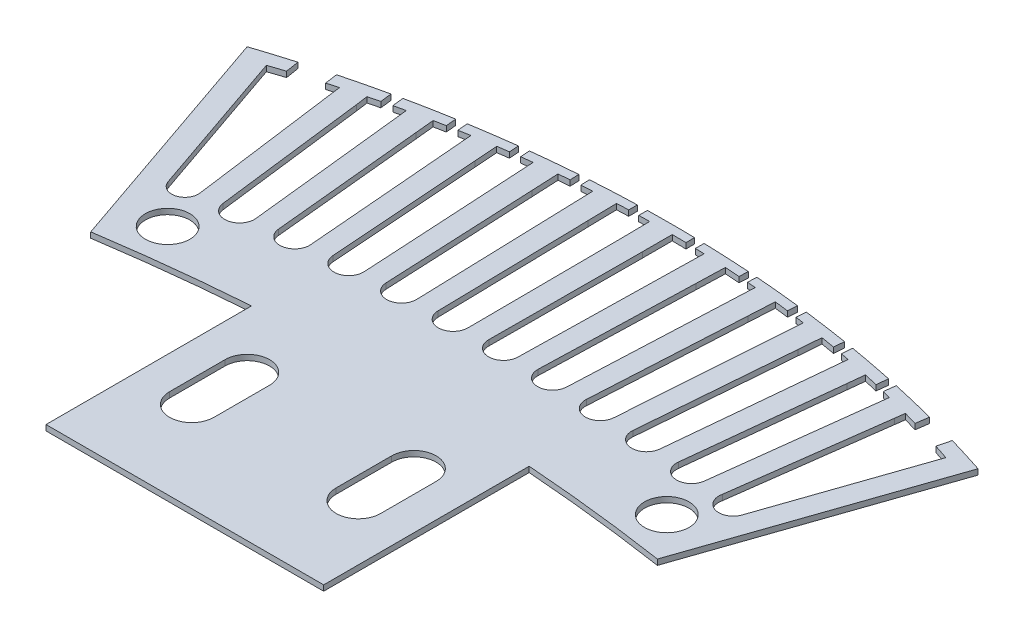
SolidWorks part; units mm, degrees
material "Galvanized Steel"
ref_plane "Front Plane" through (0, 0, 0) normal (0, 0, 1) x (1, 0, 0)
ref_plane "Top Plane" through (0, 0, 0) normal (0, 1, 0) x (1, 0, 0)
ref_plane "Right Plane" through (0, 0, 0) normal (1, 0, 0) x (0, 0, -1)
sketch "Sketch1" plane through (0, 0, 0) normal (0, 1, 0) x (1, 0, 0)
  line L0 (-1000, 0) -> (335, 0) construction
  line L1 (0, -681.9239) -> (0, 0) construction
  line L2 (-500, -866.0254) -> (24500, 42435.2448) construction
  line L3 (-500, 866.0254) -> (24500, -42435.2448) construction
  line L94 (65.8024, 379.335) -> (51.0159, 336.3919)
  line L247 (-65.8024, 379.335) -> (-51.0159, 336.3919)
  line L252 (-45.727, 348.0815) -> (-42.7621, 333.287) construction
  line L253 (0, -1000) -> (0, 49000) construction
  line L254 (-58.4419, 379.0785) -> (-58.8238, 381.4977)
  line L261 (-25, 339.3186) -> (-25, 302.3186)
  line L262 (-25, 302.3186) -> (25, 302.3186)
  line L263 (25, 339.3186) -> (25, 302.3186)
  line L280 (-61.1702, 378.1684) -> (-51.8767, 351.178)
  line L288 (-50.8939, 379.6161) -> (-47.2288, 352.2783)
  line L291 (-46.9266, 380.1269) -> (-43.5472, 352.7523)
  line L301 (58.4908, 379.0626) -> (59.0948, 381.4187)
  line L302 (-41.2051, 380.7896) -> (-38.2377, 353.3673)
  line L308 (-37.2261, 381.1992) -> (-34.5453, 353.7473)
  line L309 (-31.4895, 381.7158) -> (-29.2218, 354.2268)
  line L315 (-27.5014, 382.0239) -> (-25.5209, 354.5127)
  line L316 (-21.7536, 382.3943) -> (-20.187, 354.8564)
  line L322 (-17.7589, 382.6006) -> (-16.48, 355.0478)
  line L323 (-12.0035, 382.8244) -> (-11.139, 355.2555)
  line L329 (-8.0048, 382.9288) -> (-7.4284, 355.3525)
  line L330 (-2.2456, 383.0059) -> (-2.0838, 355.424)
  line L336 (1.7544, 383.0085) -> (1.6281, 355.4264)
  line L337 (7.5138, 382.9388) -> (6.9727, 355.3617)
  line L343 (11.5126, 382.8394) -> (10.6835, 355.2695)
  line L344 (17.2683, 382.623) -> (16.0247, 355.0687)
  line L350 (21.2632, 382.4218) -> (19.732, 354.882)
  line L351 (27.0115, 382.0588) -> (25.0663, 354.5451)
  line L352 (31.0001, 381.7559) -> (28.7676, 354.264)
  line L353 (36.7373, 381.2466) -> (34.0917, 353.7913)
  line L354 (40.7168, 380.8421) -> (37.7846, 353.416)
  line L358 (46.4391, 380.1868) -> (43.0949, 352.8079)
  line L373 (50.407, 379.6811) -> (46.777, 352.3386)
  line L374 (0, 0) -> (-49.2136, 349.5919) construction
  line L375 (-53.3884, 383.0131) -> (-53.0712, 380.7369)
  line L376 (61.1702, 378.1684) -> (51.8767, 351.178)
  line L377 (-45.4809, 384.9235) -> (-45.2357, 382.8479)
  line L378 (-43.5005, 383.2669) -> (-43.7316, 385.3027)
  line L379 (-35.5666, 384.9644) -> (-35.7398, 386.8388)
  line L380 (-33.8121, 385.292) -> (-33.9739, 387.1353)
  line L381 (-25.8013, 386.5717) -> (-25.9162, 388.2933)
  line L382 (-24.0323, 386.8069) -> (-24.1379, 388.5062)
  line L383 (-15.9663, 387.6655) -> (-16.0329, 389.283)
  line L385 (-6.0052, 388.2457) -> (-6.0052, 389.8087)
  line L390 (14.2976, 387.7995) -> (14.3915, 389.402)
  line L391 (-14.1876, 387.8078) -> (-14.2462, 389.4119)
  line L392 (-15, 302.3186) -> (-15, 318.5686) construction
  line L393 (-19, 328.5686) -> (-19, 318.5686)
  line L395 (-4.2458, 389.8516) -> (-4.2458, 388.2934)
  line L396 (4.2458, 389.8516) -> (4.2458, 388.2934)
  line L397 (6.0052, 388.2457) -> (6.0052, 389.8087)
  line L399 (15.9663, 387.6655) -> (16.0329, 389.283)
  line L400 (24.0323, 386.8069) -> (24.1379, 388.5062)
  line L401 (25.8013, 386.5717) -> (25.9162, 388.2933)
  line L402 (33.8121, 385.292) -> (33.9739, 387.1353)
  line L403 (35.5666, 384.9644) -> (35.7398, 386.8388)
  line L404 (43.5005, 383.2669) -> (43.7316, 385.3027)
  line L405 (45.4809, 384.9235) -> (45.2357, 382.8478)
  line L406 (53.3884, 383.0131) -> (53.0712, 380.7369)
  line L407 (-11, 328.5686) -> (-11, 318.5686)
  line L408 (19, 328.5686) -> (19, 318.5686)
  line L409 (11, 328.5686) -> (11, 318.5686)
  line L410 (-50.8939, 379.6161) -> (-51.1192, 381.2967)
  line L411 (-46.9266, 380.1269) -> (-47.2288, 382.345)
  line L412 (-41.2051, 380.7896) -> (-41.5226, 383.7235)
  line L413 (-37.2261, 381.1992) -> (-37.5555, 384.5722)
  line L414 (-31.4895, 381.7158) -> (-31.8136, 385.6443)
  line L415 (-27.5014, 382.0239) -> (-27.8081, 386.2841)
  line L416 (-21.7536, 382.3943) -> (-22.0187, 387.0541)
  line L417 (-17.7589, 382.6006) -> (-17.9855, 387.4834)
  line L418 (-12.0035, 382.8244) -> (-12.1596, 387.9495)
  line L419 (-8.0048, 382.9288) -> (-8.1143, 388.1668)
  line L420 (7.5138, 382.9388) -> (7.6168, 388.1875)
  line L421 (11.5126, 382.8394) -> (11.6672, 387.9806)
  line L422 (17.2683, 382.623) -> (17.4897, 387.5301)
  line L423 (21.2632, 382.4218) -> (21.524, 387.1115)
  line L424 (27.0115, 382.0588) -> (27.3154, 386.3568)
  line L425 (31.0001, 381.7559) -> (31.3226, 385.7275)
  line L426 (36.7373, 381.2466) -> (37.0672, 384.6706)
  line L427 (40.7168, 380.8421) -> (41.0365, 383.8323)
  line L428 (46.4391, 380.1868) -> (46.7187, 382.4759)
  line L429 (50.407, 379.6811) -> (50.64, 381.4306)
  line L430 (-2.2456, 383.0059) -> (-2.3106, 388.327)
  line L431 (1.7544, 383.0085) -> (1.7544, 388.3329)
  arc A44 (-167.5, 290.1185) -> (167.5, 290.1185) centre (0, 0) ccw construction
  circle A114 centre (-44.941, 344.1595) radius 4
  circle A115 centre (44.941, 344.1595) radius 4
  arc A145 (-47.2288, 352.2783) -> (-49.2136, 349.5919) centre (-49.6075, 351.9594) cw
  arc A146 (-51.8767, 351.178) -> (-49.2136, 349.5919) centre (-49.6075, 351.9594) ccw
  arc A149 (-19, 318.5686) -> (-11, 318.5686) centre (-15, 318.5686) ccw
  arc A163 (-43.5472, 352.7523) -> (-38.2377, 353.3673) centre (-40.8925, 353.0598) ccw
  arc A164 (-34.5453, 353.7473) -> (-29.2218, 354.2268) centre (-31.8836, 353.9871) ccw
  arc A165 (-25.5209, 354.5127) -> (-20.187, 354.8564) centre (-22.854, 354.6845) ccw
  arc A166 (-16.48, 355.0478) -> (-11.139, 355.2555) centre (-13.8095, 355.1517) ccw
  arc A167 (-7.4284, 355.3525) -> (-2.0838, 355.424) centre (-4.7561, 355.3882) ccw
  arc A168 (1.6281, 355.4264) -> (6.9727, 355.3617) centre (4.3004, 355.394) ccw
  arc A169 (10.6835, 355.2695) -> (16.0247, 355.0687) centre (13.3541, 355.1691) ccw
  arc A170 (19.732, 354.882) -> (25.0663, 354.5451) centre (22.3991, 354.7135) ccw
  arc A171 (28.7676, 354.264) -> (34.0917, 353.7913) centre (31.4296, 354.0277) ccw
  arc A172 (37.7846, 353.416) -> (43.0949, 352.8079) centre (40.4397, 353.1119) ccw
  arc A173 (46.777, 352.3386) -> (51.8767, 351.178) centre (49.3269, 351.7583) ccw
  arc A176 (-38.2377, 353.3673) -> (-40.2903, 350.7324) centre (-40.6238, 353.1091) cw [skipped]
  arc A177 (-29.2218, 354.2268) -> (-31.3409, 351.6451) centre (-31.6137, 354.0295) cw [skipped]
  arc A178 (-20.187, 354.8564) -> (-22.3712, 352.3294) centre (-22.5831, 354.7201) cw [skipped]
  arc A179 (-11.139, 355.2555) -> (-13.3869, 352.785) centre (-13.5379, 355.1803) cw [skipped]
  arc A180 (43.0949, 352.8079) -> (40.497, 350.7086) centre (40.7126, 353.0989) cw [skipped]
  arc A181 (34.0917, 353.7913) -> (31.5481, 351.6265) centre (31.7027, 354.0215) cw [skipped]
  arc A182 (25.0663, 354.5451) -> (22.5787, 352.3162) centre (22.6723, 354.7144) cw [skipped]
  arc A183 (16.0247, 355.0687) -> (13.5947, 352.7771) centre (13.6272, 355.1769) cw [skipped]
  arc A184 (6.9727, 355.3617) -> (4.6019, 353.009) centre (4.5732, 355.4088) cw [skipped]
  arc A185 (-2.0838, 355.424) -> (-4.3939, 353.0116) centre (-4.4838, 355.4099) cw [skipped]
  arc A190 (-176.5195, 305.7407) -> (55.2501, 348.6889) centre (0, 0) ccw construction
  arc A233 (-11, 328.5686) -> (-19, 328.5686) centre (-15, 328.5686) ccw
  arc A234 (11, 328.5686) -> (19, 328.5686) centre (15, 328.5686) cw
  arc A235 (19, 318.5686) -> (11, 318.5686) centre (15, 318.5686) cw
  arc A237 (-58.8238, 381.4977) -> (-65.8024, 379.335) centre (0, 179.3475) ccw
  arc A238 (-45.4809, 384.9235) -> (-53.3884, 383.0131) centre (0, 179.3475) ccw
  arc A239 (-35.7398, 386.8388) -> (-43.7316, 385.3027) centre (0, 179.3475) ccw
  arc A240 (-25.9162, 388.2933) -> (-33.9739, 387.1353) centre (0, 179.3475) ccw
  arc A241 (-16.0329, 389.283) -> (-24.1379, 388.5062) centre (0, 179.3475) ccw
  arc A242 (-6.0052, 389.8087) -> (-14.2462, 389.4119) centre (0, 179.3475) ccw
  arc A243 (4.2458, 389.8516) -> (-4.2458, 389.8516) centre (0, 179.3475) ccw
  arc A244 (14.3915, 389.402) -> (6.0052, 389.8087) centre (0, 179.3475) ccw
  arc A245 (24.1379, 388.5062) -> (16.0329, 389.283) centre (0, 179.3475) ccw
  arc A246 (33.9739, 387.1353) -> (25.9162, 388.2933) centre (0, 179.3475) ccw
  arc A247 (43.7316, 385.3027) -> (35.7398, 386.8388) centre (0, 179.3475) ccw
  arc A248 (53.3884, 383.0131) -> (45.4809, 384.9235) centre (0, 179.3475) ccw
  arc A249 (65.8024, 379.335) -> (59.0948, 381.4187) centre (0, 179.3475) ccw
  arc A250 (-25, 339.3186) -> (-51.0159, 336.3919) centre (0, 0) ccw
  arc A251 (25, 339.3186) -> (51.0159, 336.3919) centre (0, 0) cw
  arc A252 (-6.0052, 388.2457) -> (-8.1143, 388.1668) centre (0, 199.3411) ccw
  arc A253 (6.0052, 388.2457) -> (7.6168, 388.1875) centre (0, 199.3411) cw
  arc A254 (41.0365, 383.8323) -> (43.5005, 383.2669) centre (0, 199.3411) cw
  arc A255 (45.2357, 382.8478) -> (46.7187, 382.4759) centre (0, 199.3411) cw
  arc A256 (50.64, 381.4306) -> (53.0712, 380.7369) centre (0, 199.3411) cw
  arc A257 (58.4908, 379.0626) -> (61.1702, 378.1684) centre (0, 199.3411) cw
  arc A258 (35.5666, 384.9644) -> (37.0672, 384.6706) centre (0, 199.3411) cw
  arc A259 (31.3226, 385.7275) -> (33.8121, 385.292) centre (0, 199.3411) cw
  arc A260 (25.8013, 386.5717) -> (27.3154, 386.3568) centre (0, 199.3411) cw
  arc A261 (21.524, 387.1115) -> (24.0323, 386.8069) centre (0, 199.3411) cw
  arc A262 (15.9663, 387.6655) -> (17.4897, 387.5301) centre (0, 199.3411) cw
  arc A263 (11.6672, 387.9806) -> (14.2976, 387.7995) centre (0, 199.3411) cw
  arc A264 (-12.1596, 387.9495) -> (-14.1876, 387.8078) centre (0, 199.3411) ccw
  arc A265 (-15.9663, 387.6655) -> (-17.9855, 387.4834) centre (0, 199.3411) ccw
  arc A266 (-22.0187, 387.0541) -> (-24.0323, 386.8069) centre (0, 199.3411) ccw
  arc A267 (-25.8013, 386.5717) -> (-27.8081, 386.2841) centre (0, 199.3411) ccw
  arc A268 (-31.8136, 385.6443) -> (-33.8121, 385.292) centre (0, 199.3411) ccw
  arc A269 (-35.5666, 384.9644) -> (-37.5555, 384.5722) centre (0, 199.3411) ccw
  arc A270 (-41.5226, 383.7235) -> (-43.5005, 383.2669) centre (0, 199.3411) ccw
  arc A271 (-45.2357, 382.8479) -> (-47.2288, 382.345) centre (0, 199.3411) ccw
  arc A272 (-51.1192, 381.2967) -> (-53.0712, 380.7369) centre (0, 199.3411) ccw
  arc A273 (-58.4419, 379.0785) -> (-61.1702, 378.1684) centre (0, 199.3411) ccw
  arc A274 (-4.2458, 388.2934) -> (-2.3106, 388.327) centre (0, 199.3411) cw
  arc A275 (1.7544, 388.3329) -> (4.2458, 388.2934) centre (0, 199.3411) cw
  point P60 (0, 0)
  point P61 (0, 0)
  point P69 (0, 0)
  point P70 (0, 0)
  point P72 (0, 0)
  point P79 (0, 0)
  point P105 (0, 0)
  point P137 (0, 0)
  dimension "D2" = 11
  dimension "D9" = 8
  dimension "D15" = 4
  dimension "D10" = 38
  dimension "D11" = 8
  dimension "D33" = 10
  dimension "D26" = 2.6725
  dimension "D27" = 2.6725
  dimension "D28" = 8
  dimension "D4" = 189
  dimension "D6" = 50
  dimension "D7" = 15
  dimension "D12" = 37
  dimension "D13" = 16.25
  dimension "385" = 385
  dimension "D30" = 30
extrude "Boss-Extrude1" add sketch "Sketch1" along normal mid plane 1
